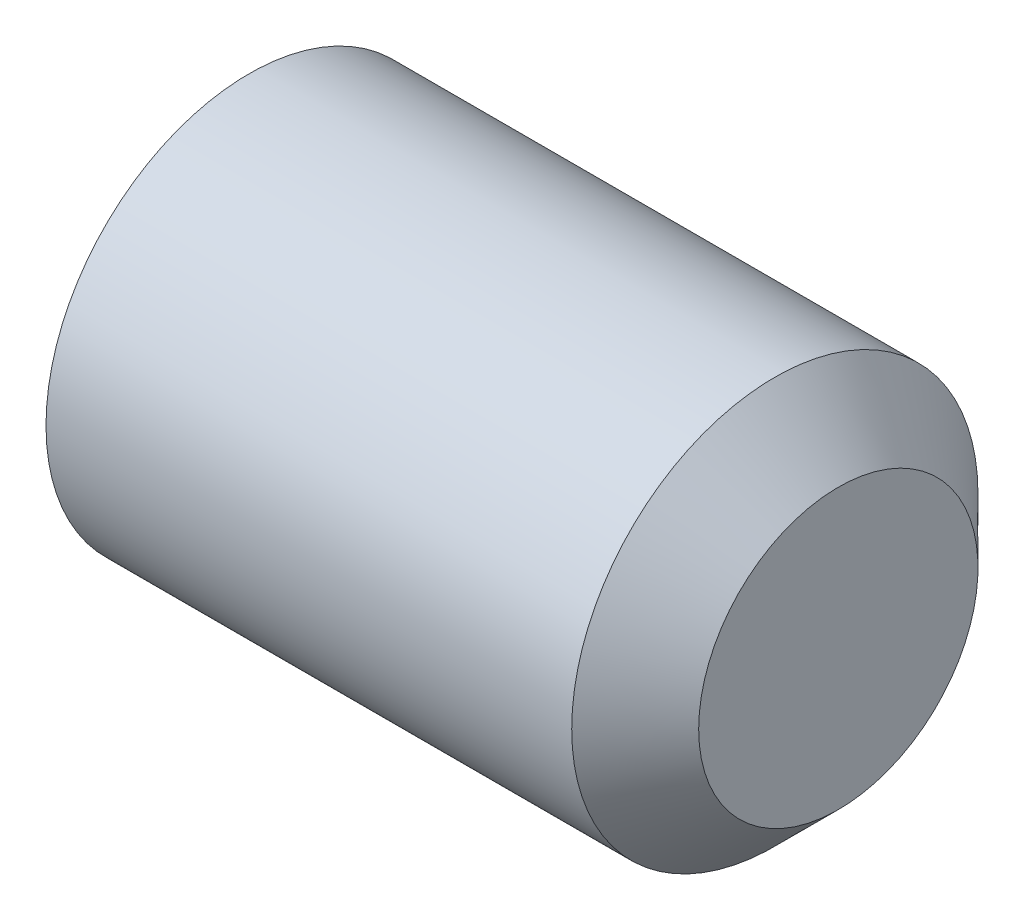
SolidWorks part; units mm, degrees
revolve "BaseBody" add sketch "BodySke" angle 360 about L5
sketch "BodySke" plane through (0, 0, 0) normal (0, 0, 1) x (1, 0, 0)
  line L0 (0, 0) -> (0, 3.3095)
  line L1 (0, 3.3095) -> (0.3987, 4)
  line L2 (0.3987, 4) -> (10.75, 4)
  line L3 (10.75, 4) -> (12, 2.75)
  line L4 (12, 0) -> (0, 0)
  line L5 (-12.7, 0) -> (88.9, 0) construction
  line L6 (12, 2.75) -> (12, 0)
  line L7 (12, 2.75) -> (12, 12.275) construction
  line L8 (0, -3.3095) -> (0.3987, -4) construction
  line L9 (1.25, 15.875) -> (1.25, -3.175) construction
  line L10 (10.75, -4) -> (12, -2.75) construction
  dimension "Diameter" = 8
  dimension "Drive_ch_ang" = 60
  dimension "Minor_dia" = 6.619
  dimension "Cup_nose_ang" = 45
  dimension "Cup_dia" = 5.5
  dimension "Length" = 12
  dimension "Advance" = 1.25
cosmetic thread "ThreadCosmetic" [suppressed] parameters "Thread_minor"=6.619
ref_plane "Plane1" through (0, 0, 0) normal (0, 0, 1) x (1, 0, 0)
ref_plane "Plane2" through (0, 0, 0) normal (0, 1, 0) x (1, 0, 0)
ref_plane "Plane3" through (0, 0, 0) normal (1, 0, 0) x (0, 0, -1)
sketch "Sketch2" plane through (0, 0, 0) normal (-1, 0, 0) x (0, 0, 1)
  line L0 (1.1547, 2) -> (-1.1547, 2)
  line L1 (-1.1547, 2) -> (-2.3094, 0)
  line L2 (1.1547, 2) -> (2.3094, 0)
  line L3 (1.1547, -2) -> (2.3094, 0)
  line L4 (1.1547, -2) -> (-1.1547, -2)
  line L5 (-1.1547, -2) -> (-2.3094, 0)
  dimension "Hex_size" = 4
  dimension "D2" = 2
  dimension "D3" = 2
extrude "Hex" cut sketch "Sketch2" against normal blind 5
sketch "ThdSchSke" plane through (0, 0, 0) normal (0, 0, 1) x (1, 0, 0)
  line L0 (0.3987, -3.3095) -> (-0.0848, -4)
  line L1 (0.3987, -3.3095) -> (0.8822, -4)
  line L2 (0.8822, -4) -> (0.8822, -5)
  line L3 (-3.175, 0) -> (5.1513, 0) construction
  line L5 (0.8822, -5) -> (-0.0848, -5)
  line L6 (-0.0848, -5) -> (-0.0848, -4)
  line L8 (0.3987, 4) -> (0.3987, -4) construction
  dimension "Thread_minor" = 6.619
  dimension "Diameter" = 8
revolve "ThreadSchematic" [suppressed] cut sketch "ThdSchSke" angle 360 about L3
pattern_linear "ThdSchPat" [suppressed]
equation "\"D2@Sketch2\" = \"Hex_size@Sketch2\" / 2"
equation "\"D3@Sketch2\" = \"Hex_size@Sketch2\" / 2"
equation "\"Thread_minor@ThreadCosmetic\" = \"Minor_dia@BodySke\""
equation "\"Thread_minor@ThdSchSke\" = \"Thread_minor@ThreadCosmetic\""
equation "\"Diameter@ThdSchSke\" = \"Diameter@BodySke\""
equation "\"Overcut@ThdSchSke\" = \"Diameter@BodySke\" * 1.25"
equation "\"Num_threads@ThdSchPat\" = int( (\"Length@BodySke\" - ( ( ( \"Diameter@BodySke\" - \"Minor_dia@BodySke\" ) * 0.5 ) / tan( \"Drive_ch_ang@BodySke\" * 0.017453292 ) ) - ( ( ( \"Diameter@BodySke\" - \"Cup_dia@BodySke\" ) * 0.5 ) * tan( \"Cup_nose_ang@BodySke\" * 0.017453292 ) ) ) / \"Advance@BodySke\" + 0.999 )  + 1"
equation "\"Advance@ThdSchPat\" = (\"Length@BodySke\" - ( ( ( \"Diameter@BodySke\" - \"Minor_dia@BodySke\" ) * 0.5 ) / tan( \"Drive_ch_ang@BodySke\" * 0.017453292 ) ) - ( ( ( \"Diameter@BodySke\" - \"Cup_dia@BodySke\" ) * 0.5 ) * tan( \"Cup_nose_ang@BodySke\" * 0.017453292 ) ) ) /  (\"Num_threads@ThdSchPat\" - 1) 'relax it"
equation "' \"Num_threads@ThdSchPat\" = \"Num_threads@ThdSchPat\" - sgn( \"Num_threads@ThdSchPat\" - 1) '---chamfered tips only---"
